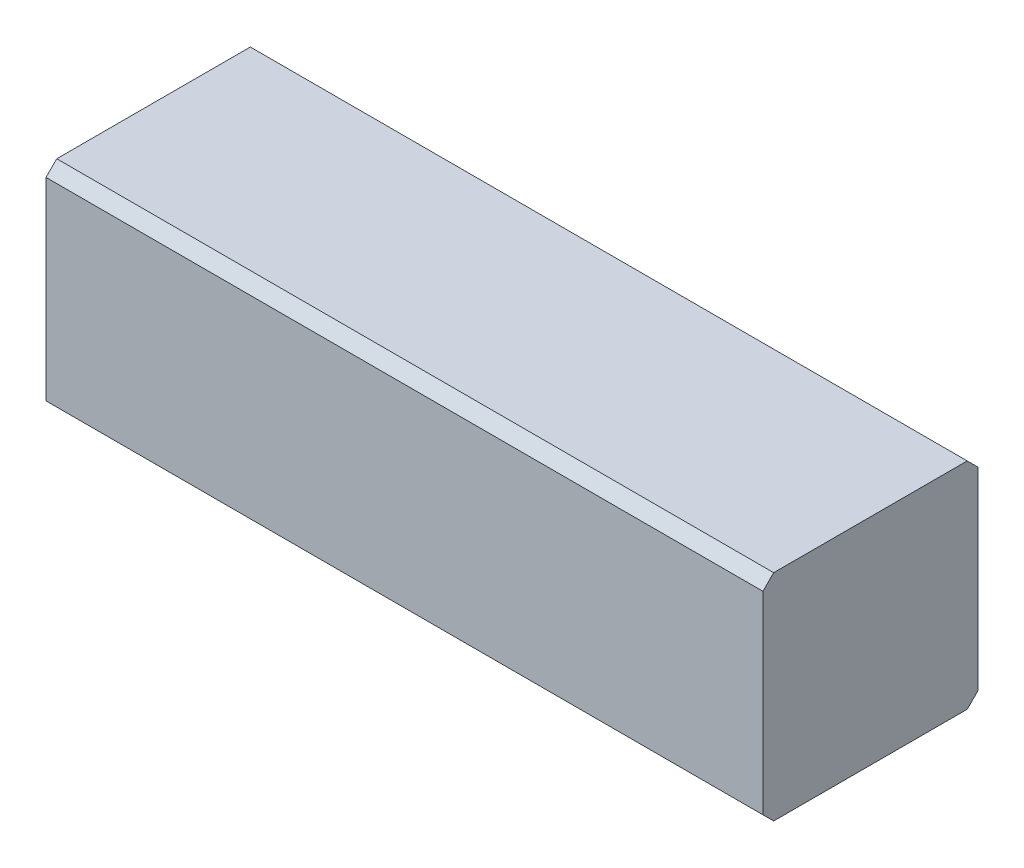
SolidWorks part; units mm, degrees
material "Alloy Steel"
ref_plane "Front Plane" through (0, 0, 0) normal (0, 0, 1) x (1, 0, 0)
ref_plane "Top Plane" through (0, 0, 0) normal (0, 1, 0) x (1, 0, 0)
ref_plane "Right Plane" through (0, 0, 0) normal (1, 0, 0) x (0, 0, -1)
sketch "Sketch1" plane through (0, 0, 0) normal (1, 0, 0) x (0, 0, -1)
  line L0 (-1.35, 1.5) -> (-1.5, 1.35)
  line L1 (-1.35, 1.5) -> (1.35, 1.5)
  line L2 (-1.5, 1.35) -> (-1.5, -1.35)
  line L3 (-1.35, -1.5) -> (1.35, -1.5)
  line L4 (1.5, 1.35) -> (1.5, -1.35)
  line L5 (-1.5, 1.5) -> (1.5, -1.5) construction
  line L6 (-1.5, -1.5) -> (1.5, 1.5) construction
  line L7 (-1.5, -1.35) -> (-1.35, -1.5)
  line L8 (1.35, -1.5) -> (1.5, -1.35)
  line L9 (1.35, 1.5) -> (1.5, 1.35)
  point P0 (0, 0)
  dimension "D1" = 3
  dimension "D2" = 3
extrude "Boss-Extrude1" add sketch "Sketch1" along normal blind 10
